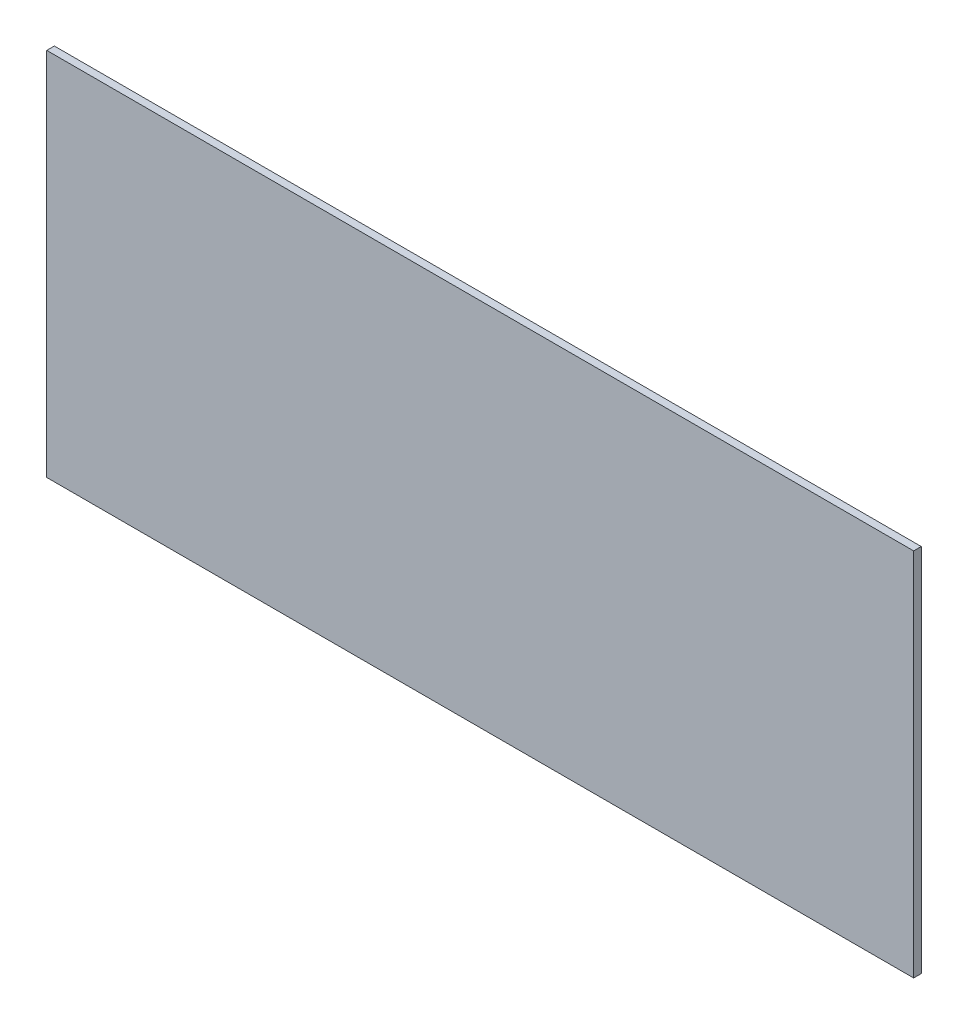
SolidWorks part; units mm, degrees
ref_plane "Alzado" through (0, 0, 0) normal (0, 0, 1) x (1, 0, 0)
ref_plane "Planta" through (0, 0, 0) normal (0, 1, 0) x (1, 0, 0)
ref_plane "Vista lateral" through (0, 0, 0) normal (1, 0, 0) x (0, 0, -1)
sketch "Croquis2" plane through (0, 0, 0) normal (0, 0, 1) x (1, 0, 0)
  line L0 (0, -55) -> (0, 55) construction
  line L1 (-57.15, 24.384) -> (57.15, 24.384)
  line L2 (-57.15, 24.384) -> (-57.15, -24.384)
  line L3 (-57.15, -24.384) -> (57.15, -24.384)
  line L4 (57.15, 24.384) -> (57.15, -24.384)
  line L5 (55, 0) -> (-55, 0) construction
  point P4 (-57.15, 0)
  point P5 (0, 24.384)
  dimension "D1" = 114.3
  dimension "D2" = 48.768
extrude "Saliente-Extruir1" add sketch "Croquis2" along normal mid plane 1
